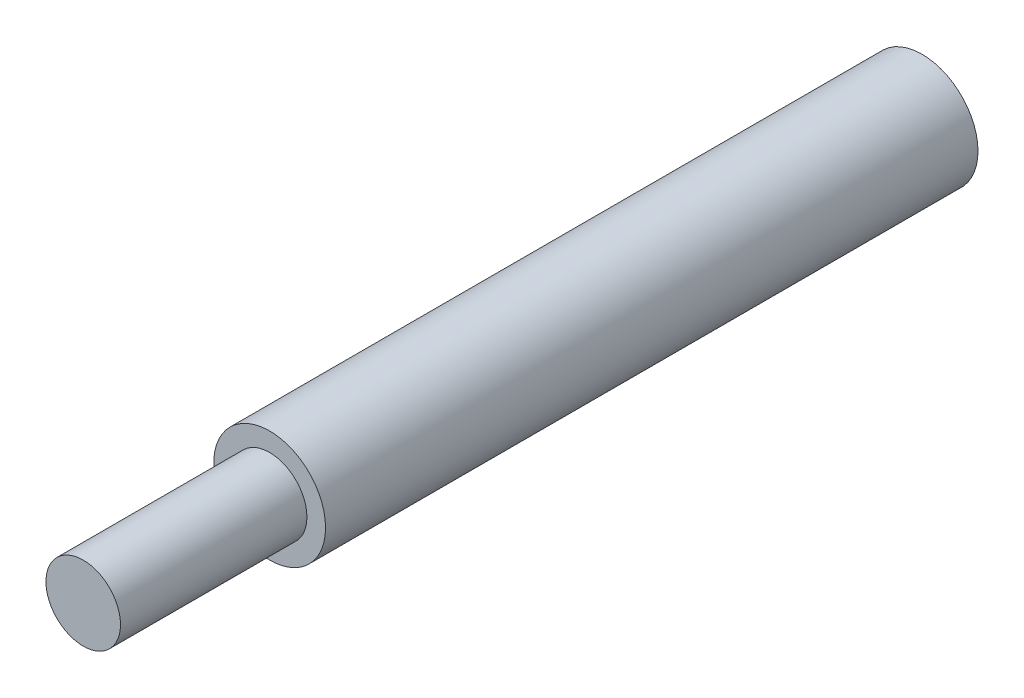
SolidWorks part; units mm, degrees
ref_plane "正面" through (0, 0, 0) normal (0, 0, 1) x (1, 0, 0)
ref_plane "平面" through (0, 0, 0) normal (0, 1, 0) x (1, 0, 0)
ref_plane "右側面" through (0, 0, 0) normal (1, 0, 0) x (0, 0, -1)
sketch "Sketch1" plane through (0, 0, 0) normal (0, 0, 1) x (1, 0, 0)
  circle A0 centre (0, 0) radius 6
  dimension "D1" = 12
extrude "Boss-Extrude1" add sketch "Sketch1" along normal blind 70
sketch "Sketch2" plane through (0, 0, 70) normal (0, 0, 1) x (1, 0, 0)
  circle A0 centre (0, 0) radius 4
  dimension "D1" = 8
extrude "Boss-Extrude2" add sketch "Sketch2" along normal blind 20
